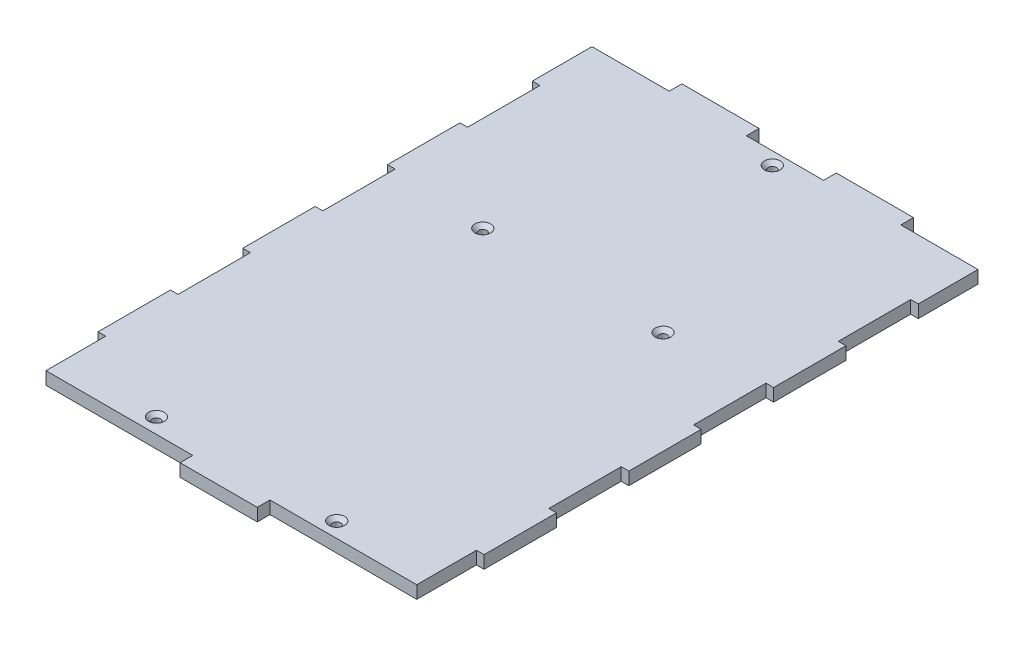
SolidWorks part; units mm, degrees
ref_plane "Front Plane" through (0, 0, 0) normal (0, 0, 1) x (1, 0, 0)
ref_plane "Top Plane" through (0, 0, 0) normal (0, 1, 0) x (1, 0, 0)
ref_plane "Right Plane" through (0, 0, 0) normal (1, 0, 0) x (0, 0, -1)
sketch "Sketch1" plane through (0, 0, 0) normal (0, 1, 0) x (1, 0, 0)
  line L0 (0, -114) -> (-15.2, -114)
  line L1 (-76, -114) -> (76, -114) construction
  line L2 (-76, -114) -> (-76, 114) construction
  line L3 (-76, 114) -> (76, 114) construction
  line L4 (76, -114) -> (76, 114) construction
  line L5 (0, 109) -> (0, -114)
  line L6 (-76, 0) -> (76, 0) construction
  line L7 (-15.2, -114) -> (-15.2, -109)
  line L8 (-15.2, -109) -> (-73, -109)
  line L25 (-73, -109) -> (-73, -85.5)
  line L26 (-73, -85.5) -> (-76, -85.5)
  line L27 (-76, -57) -> (-73, -57)
  line L28 (-73, -57) -> (-73, -28.5)
  line L29 (-73, -28.5) -> (-76, -28.5)
  line L30 (-76, -28.5) -> (-76, 0)
  line L31 (-76, -85.5) -> (-76, -57)
  line L32 (-76, 0) -> (-73, 0)
  line L33 (-73, 0) -> (-73, 28.5)
  line L34 (-73, 28.5) -> (-76, 28.5)
  line L35 (-76, 28.5) -> (-76, 57)
  line L36 (-76, 57) -> (-73, 57)
  line L37 (-73, 57) -> (-73, 85.5)
  line L38 (-73, 85.5) -> (-76, 85.5)
  line L42 (-76, 109) -> (-76, 85.5)
  line L43 (0, 109) -> (-15.2, 109)
  line L44 (-15.2, 109) -> (-15.2, 114)
  line L45 (-15.2, 114) -> (-45.6, 114)
  line L46 (-45.6, 114) -> (-45.6, 109)
  line L47 (-45.6, 109) -> (-76, 109)
  point P128 (0, 0)
  dimension "D1" = 152
  dimension "D2" = 228
  dimension "D5" = 5
  dimension "D3" = 60.8
  dimension "D4" = 28.5
  dimension "D6" = 3
  dimension "D7" = 28.5
  dimension "D8" = 28.5
  dimension "D9" = 28.5
  dimension "D10" = 28.5
  dimension "D11" = 28.5
  dimension "D12" = 28.5
  dimension "D13" = 5
  dimension "D14" = 30.4
extrude "Boss-Extrude1" add sketch "Sketch1" along normal blind 5
mirror "Mirror1" about plane through (0, 5, 0) normal (1, 0, 0) of "Boss-Extrude1"
sketch "Sketch2" plane through (0, 5, 0) normal (0, 1, 0) x (1, 0, 0)
  line L0 (15.2, 109) -> (-15.2, 109) construction
  line L1 (15.2, -109) -> (73, -109) construction
  line L2 (35.5, -103) -> (-35.5, -103) construction
  line L3 (35.5, -103) -> (35.5, 25.5) construction
  line L4 (35.5, 25.5) -> (-35.5, 25.5) construction
  line L5 (-35.5, -103) -> (-35.5, 25.5) construction
  line L6 (0, 25.5) -> (0, -103) construction
  line L7 (35.5, -38.75) -> (-35.5, -38.75) construction
  circle A0 centre (0, 104) radius 1.6
  circle A1 centre (-35.5, 25.5) radius 1.6
  circle A2 centre (35.5, 25.5) radius 1.6
  circle A3 centre (-35.5, -103) radius 1.6
  circle A4 centre (35.5, -103) radius 1.6
  point P13 (-35.5, 31.7981)
  point P225 (0, -38.75)
  dimension "D2" = 3.2
  dimension "D5" = 3.2
  dimension "D1" = 5
  dimension "D3" = 128.5
  dimension "D4" = 71
  dimension "D6" = 6
extrude "Cut-Extrude1" cut sketch "Sketch2" against normal through all
chamfer "Chamfer1" distance 1.5 5 edges at (0, 5, -102.4) (35.5, 5, -23.9) (-35.5, 5, -23.9) (35.5, 5, 104.6) (-35.5, 5, 104.6)
equation "\"3mm akryyli\"= 3mm"
equation "\"5mm akryyli\"= 5mm"
equation "\"D5@Sketch1\"=\"5mm akryyli\""
equation "\"D6@Sketch1\"=\"3mm akryyli\""
equation "\"D13@Sketch1\"=\"5mm akryyli\""
